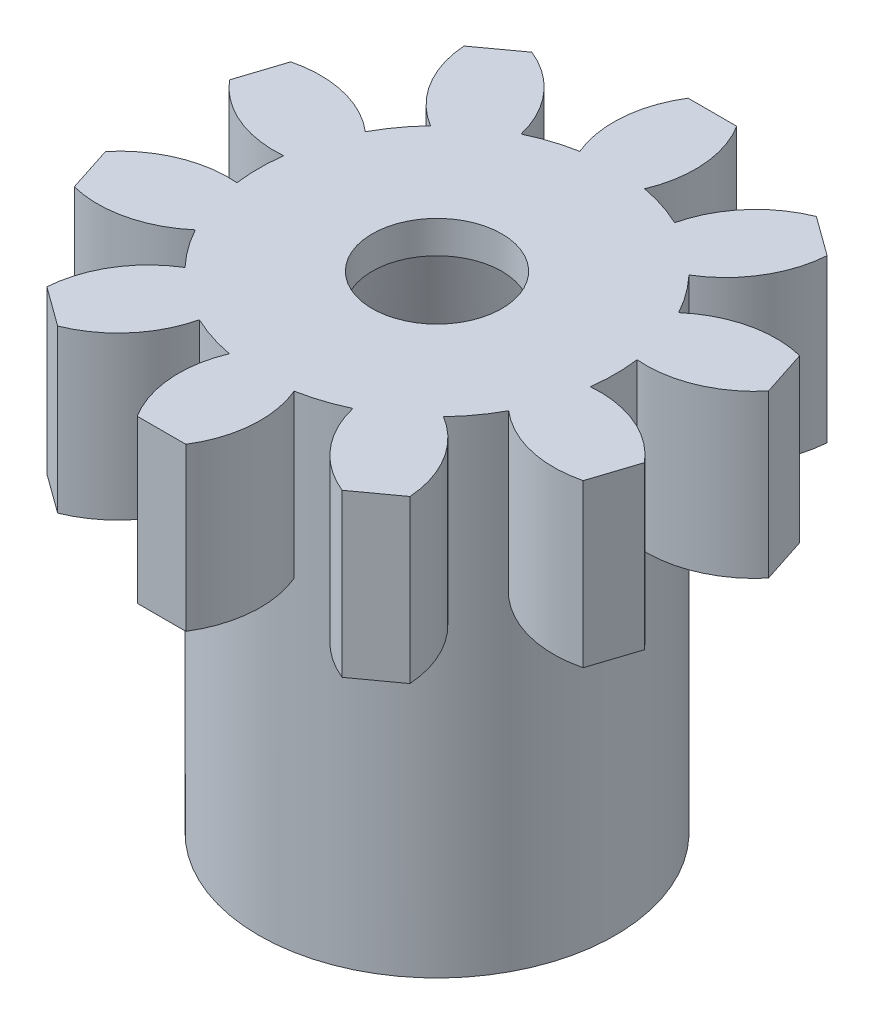
SolidWorks part; units mm, degrees
ref_plane "前视基准面" through (0, 0, 0) normal (0, 0, 1) x (1, 0, 0)
ref_plane "上视基准面" through (0, 0, 0) normal (0, 1, 0) x (1, 0, 0)
ref_plane "右视基准面" through (0, 0, 0) normal (1, 0, 0) x (0, 0, -1)
sketch "草图1" plane through (0, 0, 0) normal (0, 1, 0) x (1, 0, 0)
  circle A0 centre (0, 0) radius 5.5
extrude "凸台-拉伸1" add sketch "草图1" along normal blind 5
sketch "草图2" plane through (0, 5, 0) normal (0, 1, 0) x (-1, 0, 0)
  line L0 (-4.3894, -7.3175) -> (-5.6029, -6.4358)
  line L1 (-7.8522, -3.3399) -> (-8.3157, -1.9134)
  line L2 (-8.3157, 1.9134) -> (-7.8522, 3.3399)
  line L3 (-5.6029, 6.4358) -> (-4.3894, 7.3175)
  line L4 (-0.75, 8.5) -> (0.75, 8.5)
  line L5 (4.3894, 7.3175) -> (5.6029, 6.4358)
  line L6 (0.75, -8.5) -> (-0.75, -8.5)
  line L7 (7.8522, 3.3399) -> (8.3157, 1.9134)
  line L8 (8.3157, -1.9134) -> (7.8522, -3.3399)
  line L9 (5.6029, -6.4358) -> (4.3894, -7.3175)
  arc A0 (-1, -5.4083) -> (1, -5.4083) centre (0, 0) ccw
  arc A1 (-1, -5.4083) -> (-0.75, -8.5) centre (2.1122, -6.7126) ccw
  arc A2 (1, -5.4083) -> (0.75, -8.5) centre (-2.1122, -6.7126) cw
  arc A3 (-3.988, -3.7876) -> (-2.3699, -4.9632) centre (0, 0) ccw
  arc A4 (-3.988, -3.7876) -> (-5.6029, -6.4358) centre (-2.2368, -6.6721) ccw
  arc A5 (-2.3699, -4.9632) -> (-4.3894, -7.3175) centre (-5.6543, -4.1891) cw
  arc A6 (-5.4526, -0.7202) -> (-4.8346, -2.6223) centre (0, 0) ccw
  arc A7 (-5.4526, -0.7202) -> (-8.3157, -1.9134) centre (-5.7314, -4.0831) ccw
  arc A8 (-4.8346, -2.6223) -> (-7.8522, -3.3399) centre (-7.0368, -0.0655) cw
  arc A9 (-4.8346, 2.6223) -> (-5.4526, 0.7202) centre (0, 0) ccw
  arc A10 (-4.8346, 2.6223) -> (-7.8522, 3.3399) centre (-7.0368, 0.0655) ccw
  arc A11 (-5.4526, 0.7202) -> (-8.3157, 1.9134) centre (-5.7314, 4.0831) cw
  arc A12 (-2.3699, 4.9632) -> (-3.988, 3.7876) centre (0, 0) ccw
  arc A13 (-2.3699, 4.9632) -> (-4.3894, 7.3175) centre (-5.6543, 4.1891) ccw
  arc A14 (-3.988, 3.7876) -> (-5.6029, 6.4358) centre (-2.2368, 6.6721) cw
  arc A15 (1, 5.4083) -> (-1, 5.4083) centre (0, 0) ccw
  arc A16 (1, 5.4083) -> (0.75, 8.5) centre (-2.1122, 6.7126) ccw
  arc A17 (-1, 5.4083) -> (-0.75, 8.5) centre (2.1122, 6.7126) cw
  arc A18 (3.988, 3.7876) -> (2.3699, 4.9632) centre (0, 0) ccw
  arc A19 (3.988, 3.7876) -> (5.6029, 6.4358) centre (2.2368, 6.6721) ccw
  arc A20 (2.3699, 4.9632) -> (4.3894, 7.3175) centre (5.6543, 4.1891) cw
  arc A21 (5.4526, 0.7202) -> (4.8346, 2.6223) centre (0, 0) ccw
  arc A22 (5.4526, 0.7202) -> (8.3157, 1.9134) centre (5.7314, 4.0831) ccw
  arc A23 (4.8346, 2.6223) -> (7.8522, 3.3399) centre (7.0368, 0.0655) cw
  arc A24 (4.8346, -2.6223) -> (5.4526, -0.7202) centre (0, 0) ccw
  arc A25 (4.8346, -2.6223) -> (7.8522, -3.3399) centre (7.0368, -0.0655) ccw
  arc A26 (5.4526, -0.7202) -> (8.3157, -1.9134) centre (5.7314, -4.0831) cw
  arc A27 (2.3699, -4.9632) -> (3.988, -3.7876) centre (0, 0) ccw
  arc A28 (2.3699, -4.9632) -> (4.3894, -7.3175) centre (5.6543, -4.1891) ccw
  arc A29 (3.988, -3.7876) -> (5.6029, -6.4358) centre (2.2368, -6.6721) cw
  point P5 (0, -8.5)
  point P13 (-4.9962, -6.8766)
  point P22 (-8.084, -2.6266)
  point P30 (-8.084, 2.6266)
  point P38 (-4.9962, 6.8766)
  point P46 (0, 8.5)
  point P54 (4.9962, 6.8766)
  point P62 (8.084, 2.6266)
  point P70 (8.084, -2.6266)
  point P78 (4.9962, -6.8766)
  dimension "D1" = 10
extrude "凸台-拉伸2" add sketch "草图2" against normal up to surface (5 mm away) up to face at (0, 0, 5.5)
sketch "草图3" plane through (0, 0, 0) normal (0, -1, 0) x (1, 0, 0)
  circle A0 centre (0, 0) radius 5.5
  dimension "D1" = 11
extrude "凸台-拉伸3" add sketch "草图3" along normal blind 10
sketch "草图4" plane through (0, 0, 0) normal (0, 0, 1) x (1, 0, 0)
  line L0 (0, -10) -> (0, -3)
  line L2 (-5.5, -10) -> (5.5, -10) construction
  line L4 (0, -3) -> (0, 4)
  line L7 (0, 4) -> (0, 5)
  line L10 (-0.75, 5) -> (0.75, 5) construction
  line L11 (0, -10) -> (4.5, -10)
  line L12 (4.5, -10) -> (4.5, -3)
  line L13 (0, 4) -> (3, 4) construction
  line L14 (3, 4) -> (4.5, -3)
  line L15 (2, 5) -> (2, 4)
  line L16 (4.3894, 5) -> (2.3699, 5) construction
  line L17 (2, 5) -> (0, 5)
  line L18 (2, 4) -> (3, 4)
  dimension "D1" = 7
  dimension "D2" = 7
  dimension "D3" = 4.5
  dimension "D4" = 7
  dimension "D5" = 3
  dimension "D6" = 2
revolve "切除-旋转1" cut sketch "草图4" angle 360 about L4
